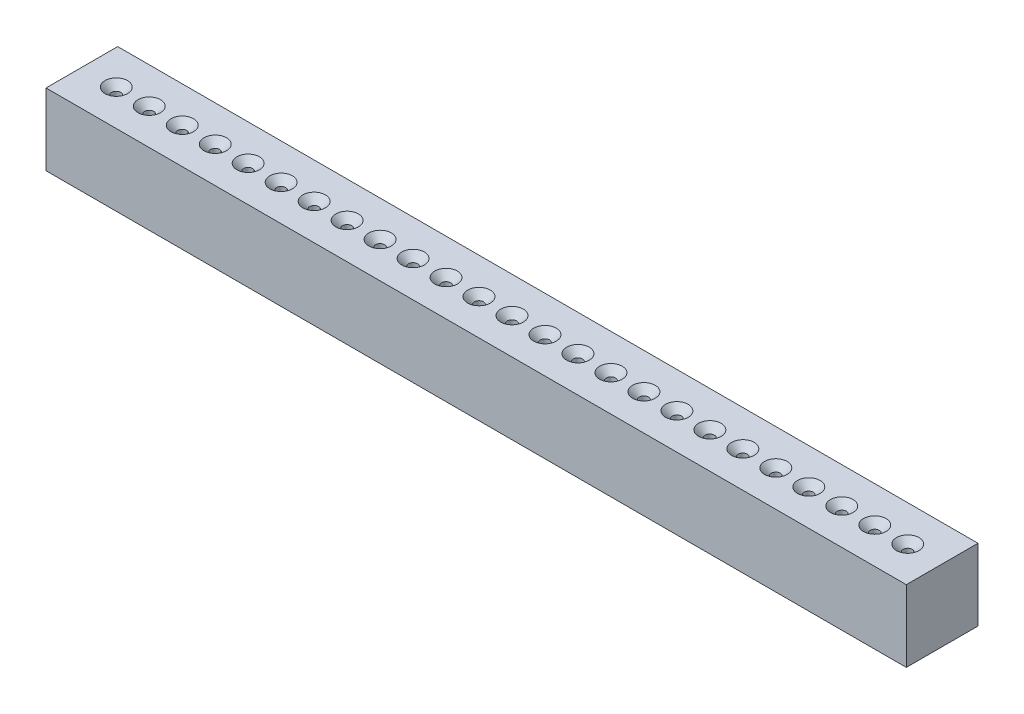
SolidWorks part; units mm, degrees
ref_plane "Front Plane" through (0, 0, 0) normal (0, 0, 1) x (1, 0, 0)
ref_plane "Top Plane" through (0, 0, 0) normal (0, 1, 0) x (1, 0, 0)
ref_plane "Right Plane" through (0, 0, 0) normal (1, 0, 0) x (0, 0, -1)
sketch "Sketch1" plane through (0, 0, 0) normal (0, 1, 0) x (1, 0, 0)
  line L1 (0, 0) -> (152.4, 0)
  line L2 (0, 0) -> (0, 12.7)
  line L3 (0, 12.7) -> (152.4, 12.7)
  line L4 (152.4, 0) -> (152.4, 12.7)
  dimension "D1" = 12.7
  dimension "D2" = 152.4
extrude "Boss-Extrude1" add sketch "Sketch1" along normal blind 12.7
hole_wizard "M2x0.4 Tapped Hole1" positions "Sketch5" profile "Sketch6" tap size "M2x0.4" standard "ANSI Metric"
sketch "Sketch5" plane through (0, 12.7, 0) normal (0, 1, 0) x (1, 0, 0)
  line L0 (152.4, 12.7) -> (0, 12.7) construction
  line L1 (0, 12.7) -> (0, 0) construction
  point P0 (6.096, 6.35)
  point P7 (11.938, 6.35)
  point P8 (17.78, 6.35)
  point P9 (23.622, 6.35)
  point P10 (29.464, 6.35)
  point P11 (35.306, 6.35)
  point P12 (41.148, 6.35)
  point P13 (46.99, 6.35)
  point P14 (52.832, 6.35)
  point P15 (58.674, 6.35)
  point P16 (64.516, 6.35)
  point P17 (70.358, 6.35)
  point P18 (76.2, 6.35)
  point P19 (82.042, 6.35)
  point P20 (87.884, 6.35)
  point P21 (93.726, 6.35)
  point P22 (99.568, 6.35)
  point P23 (105.41, 6.35)
  point P24 (111.252, 6.35)
  point P25 (117.094, 6.35)
  point P26 (122.936, 6.35)
  point P27 (128.778, 6.35)
  point P28 (134.62, 6.35)
  point P29 (140.462, 6.35)
  point P30 (146.304, 6.35)
  dimension "D2" = 6.35
  dimension "D3" = 6.096
  dimension "D4" = 5.842
  dimension "D1" = 25
sketch "Sketch6" plane through (6.096, 12.7, -6.35) normal (1, 0, 0) x (0, 0, 1)
  line L0 (0, 0) -> (0, 3.479)
  line L1 (0, 3.479) -> (0.8, 2.9983)
  line L2 (0.8, 2.9983) -> (0.8, 1.2)
  line L3 (0.8, 1.2) -> (2, 0)
  line L5 (2, 0) -> (0, 0)
  line L6 (-0.8, 1.2) -> (-2, 0) construction
  line L10 (0, 3.479) -> (-0.8, 2.9983) construction
  line L11 (0, -6.35) -> (0, 107.95) construction
  dimension "Tap Drill Dia." = 1.6
  dimension "Tap Drill Depth" = 2.9983
  dimension "Near C'Sink Dia." = 4
  dimension "Near C'Sink Angle" = 90
  dimension "Drill Angle" = 118
cosmetic thread "Hole Thread1" parameters "D1"=1.778, "D2"=2
cosmetic thread "Hole Thread2" parameters "D1"=1.778, "D2"=2
cosmetic thread "Hole Thread3" parameters "D1"=1.778, "D2"=2
cosmetic thread "Hole Thread4" parameters "D1"=1.778, "D2"=2
cosmetic thread "Hole Thread5" parameters "D1"=1.778, "D2"=2
cosmetic thread "Hole Thread6" parameters "D1"=1.778, "D2"=2
cosmetic thread "Hole Thread7" parameters "D1"=1.778, "D2"=2
cosmetic thread "Hole Thread8" parameters "D1"=1.778, "D2"=2
cosmetic thread "Hole Thread9" parameters "D1"=1.778, "D2"=2
cosmetic thread "Hole Thread10" parameters "D1"=1.778, "D2"=2
cosmetic thread "Hole Thread11" parameters "D1"=1.778, "D2"=2
cosmetic thread "Hole Thread12" parameters "D1"=1.778, "D2"=2
cosmetic thread "Hole Thread13" parameters "D1"=1.778, "D2"=2
cosmetic thread "Hole Thread14" parameters "D1"=1.778, "D2"=2
cosmetic thread "Hole Thread15" parameters "D1"=1.778, "D2"=2
cosmetic thread "Hole Thread16" parameters "D1"=1.778, "D2"=2
cosmetic thread "Hole Thread17" parameters "D1"=1.778, "D2"=2
cosmetic thread "Hole Thread18" parameters "D1"=1.778, "D2"=2
cosmetic thread "Hole Thread19" parameters "D1"=1.778, "D2"=2
cosmetic thread "Hole Thread20" parameters "D1"=1.778, "D2"=2
cosmetic thread "Hole Thread21" parameters "D1"=1.778, "D2"=2
cosmetic thread "Hole Thread22" parameters "D1"=1.778, "D2"=2
cosmetic thread "Hole Thread23" parameters "D1"=1.778, "D2"=2
cosmetic thread "Hole Thread24" parameters "D1"=1.778, "D2"=2
cosmetic thread "Hole Thread25" parameters "D1"=1.778, "D2"=2
